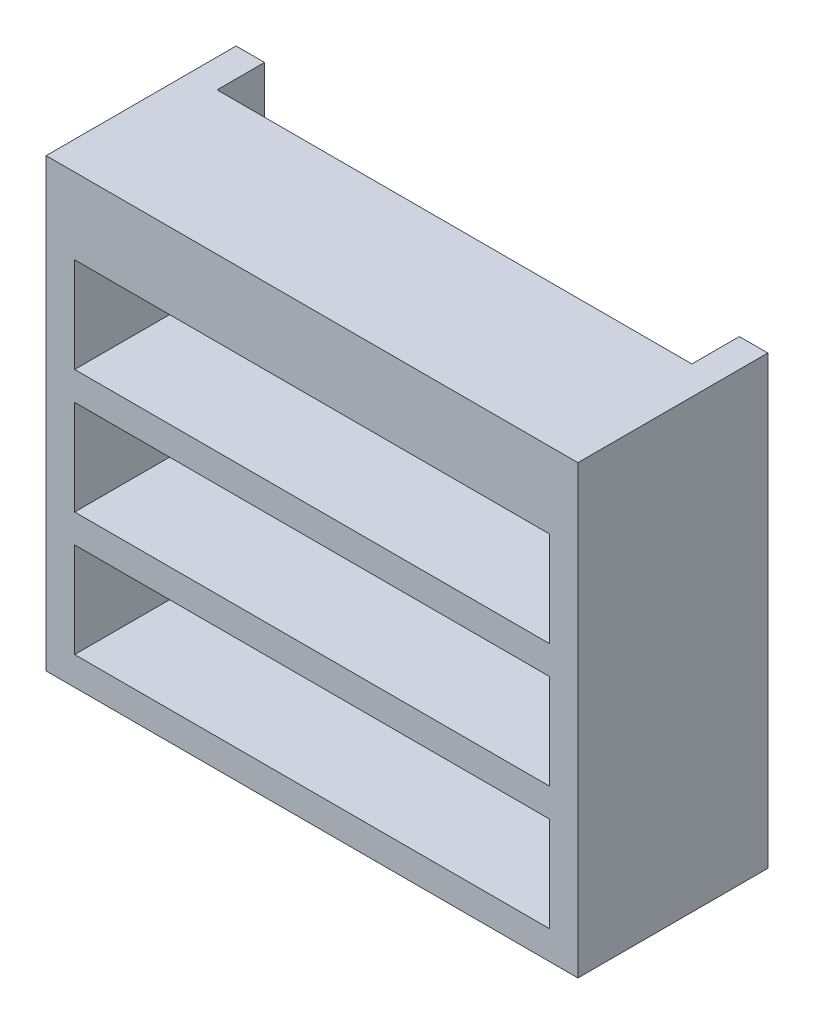
SolidWorks part; units mm, degrees
ref_plane "前视基准面" through (0, 0, 0) normal (0, 0, 1) x (1, 0, 0)
ref_plane "上视基准面" through (0, 0, 0) normal (0, 1, 0) x (1, 0, 0)
ref_plane "右视基准面" through (0, 0, 0) normal (1, 0, 0) x (0, 0, -1)
sketch "草图1" plane through (0, 0, 0) normal (0, 0, 1) x (1, 0, 0)
  line L0 (-29.1326, -10.4353) -> (20.8674, -10.4353)
  line L1 (-29.1326, 15.5647) -> (20.8674, 15.5647)
  line L2 (-29.1326, 15.5647) -> (-29.1326, -20.4353)
  line L3 (-29.1326, -20.4353) -> (20.8674, -20.4353)
  line L4 (20.8674, 15.5647) -> (20.8674, -20.4353)
  line L5 (-29.1326, -7.4353) -> (20.8674, -7.4353)
  line L6 (-29.1326, 2.5647) -> (20.8674, 2.5647)
  line L7 (-29.1326, 5.5647) -> (20.8674, 5.5647)
  dimension "D1" = 50
  dimension "D2" = 36
  dimension "D3" = 10
  dimension "D4" = 10
  dimension "D5" = 3
  dimension "D6" = 3
sketch "草图2" plane through (0, 0, 0) normal (0, 0, 1) x (1, 0, 0)
  line L0 (-29.1326, 18.5647) -> (-32.1326, 18.5647)
  line L1 (-32.1326, 18.5647) -> (-32.1326, -23.4353)
  line L2 (-32.1326, -23.4353) -> (-29.1326, -23.4353)
  line L3 (-29.1326, -23.4353) -> (23.8674, -23.4353)
  line L4 (23.8674, -23.4353) -> (23.8674, 18.5647)
  line L5 (23.8674, 18.5647) -> (-29.1326, 18.5647)
  line L6 (-29.1326, 15.5647) -> (-29.1326, 5.5647)
  line L7 (-29.1326, 5.5647) -> (20.8674, 5.5647)
  line L8 (20.8674, 5.5647) -> (20.8674, 15.5647)
  line L9 (20.8674, 15.5647) -> (-29.1326, 15.5647)
  line L10 (-29.1326, 2.5647) -> (-29.1326, -7.4353)
  line L11 (-29.1326, -7.4353) -> (20.8674, -7.4353)
  line L12 (20.8674, -7.4353) -> (20.8674, 2.5647)
  line L13 (-29.1326, 2.5647) -> (20.8674, 2.5647)
  line L14 (-29.1326, -10.4353) -> (-29.1326, -20.4353)
  line L15 (-29.1326, -20.4353) -> (20.8674, -20.4353)
  line L16 (20.8674, -20.4353) -> (20.8674, -10.4353)
  line L17 (20.8674, -10.4353) -> (-29.1326, -10.4353)
  dimension "D1" = 3
  dimension "D2" = 3
  dimension "D3" = 3
  dimension "D4" = 3
extrude "凸台-拉伸1" add sketch "草图2" along normal blind 15
sketch "草图3" plane through (0, 0, 0) normal (0, 0, -1) x (-1, 0, 0)
  line L0 (32.1326, -23.4353) -> (-23.8674, -23.4353) construction
  line L1 (32.1326, 18.5647) -> (29.1326, 18.5647)
  line L2 (32.1326, 18.5647) -> (32.1326, -23.4353)
  line L3 (32.1326, -23.4353) -> (29.1326, -23.4353)
  line L4 (29.1326, 18.5647) -> (29.1326, -23.4353)
  line L5 (-23.8674, 18.5647) -> (-20.8674, 18.5647)
  line L6 (-23.8674, 18.5647) -> (-23.8674, -23.4353)
  line L7 (-23.8674, -23.4353) -> (-20.8674, -23.4353)
  line L8 (-20.8674, 18.5647) -> (-20.8674, -23.4353)
extrude "凸台-拉伸2" add sketch "草图3" along normal blind 5
sketch "草图4" plane through (0, 18.5647, 0) normal (0, 1, 0) x (1, 0, 0)
  line L0 (20.8674, 5) -> (23.8674, 5) construction
  line L1 (-32.1326, 5) -> (-29.1326, 5)
  line L2 (-32.1326, 5) -> (-32.1326, 0)
  line L3 (-32.1326, 0) -> (-29.1326, 0)
  line L4 (-29.1326, 5) -> (-29.1326, 0)
  line L5 (20.8674, 5) -> (23.8674, 5)
  line L6 (20.8674, 5) -> (20.8674, 0)
  line L7 (20.8674, 0) -> (23.8674, 0)
  line L8 (23.8674, 5) -> (23.8674, 0)
  line L9 (20.8674, 5) -> (20.8674, 0) construction
  line L10 (23.8674, -15) -> (23.8674, 5) construction
extrude "凸台-拉伸4" add sketch "草图4" along normal blind 5
sketch "草图5" plane through (0, 18.5647, 0) normal (0, 1, 0) x (1, 0, 0)
  line L6 (23.8674, 0) -> (20.8674, 0)
  line L7 (20.8674, 0) -> (-29.1326, 0)
  line L8 (-29.1326, 0) -> (-32.1326, 0)
  line L9 (-32.1326, 0) -> (-32.1326, -15)
  line L10 (-32.1326, -15) -> (23.8674, -15)
  line L11 (23.8674, -15) -> (23.8674, 0)
  line L12 (23.8674, 0) -> (20.8674, 0)
  line L13 (20.8674, 0) -> (-29.1326, 0)
  line L14 (-29.1326, 0) -> (-32.1326, 0)
  line L15 (-32.1326, 0) -> (-32.1326, -15)
  line L16 (-32.1326, -15) -> (23.8674, -15)
  line L17 (23.8674, -15) -> (23.8674, 0)
  dimension "D1" = 0
extrude "凸台-拉伸5" add sketch "草图5" along normal blind 5
